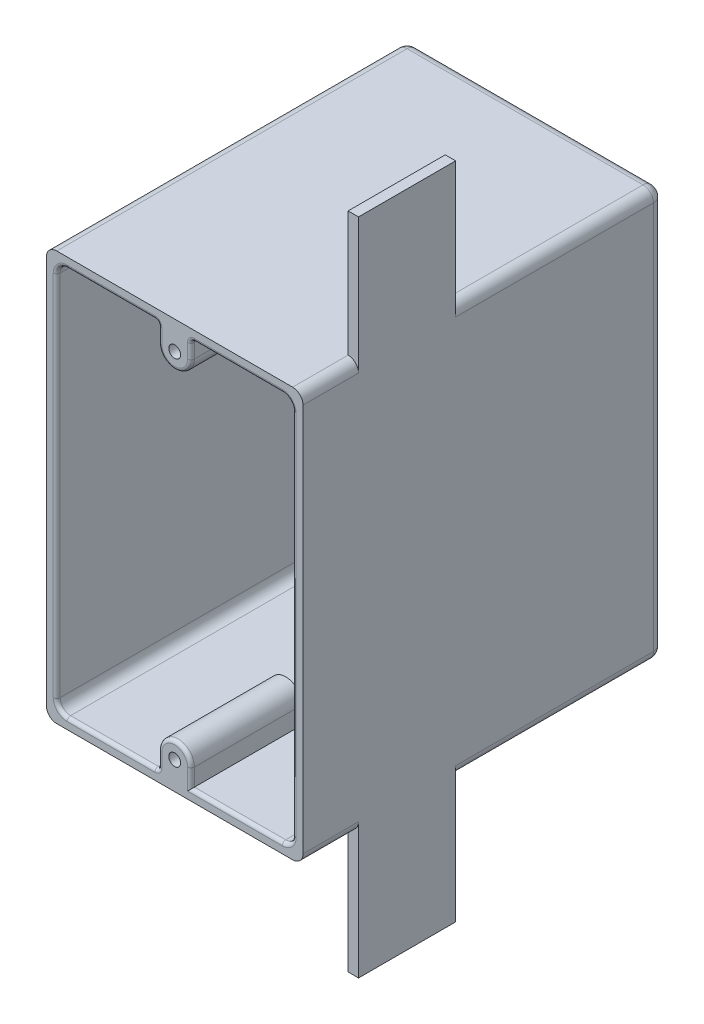
SolidWorks part; units mm, degrees
material "ABS"
ref_plane "Front" through (0, 0, 0) normal (0, 0, 1) x (1, 0, 0)
ref_plane "Top" through (0, 0, 0) normal (0, 1, 0) x (1, 0, 0)
ref_plane "Right" through (0, 0, 0) normal (1, 0, 0) x (0, 0, -1)
sketch "Sketch1" plane through (0, 0, 0) normal (0, 0, 1) x (1, 0, 0)
  line L1 (-29.3688, 46.8313) -> (29.3687, 46.8313)
  line L2 (-29.3688, 46.8313) -> (-29.3687, -46.8312)
  line L3 (-29.3687, -46.8312) -> (29.3687, -46.8312)
  line L4 (29.3687, 46.8313) -> (29.3687, -46.8312)
  line L5 (-29.3688, 46.8313) -> (29.3687, -46.8312) construction
  line L6 (-29.3687, -46.8312) -> (29.3687, 46.8313) construction
  point P0 (0, 0)
  dimension "D1" = 58.7375
  dimension "D2" = 93.6625
extrude "Back" add sketch "Sketch1" along normal blind 2.3813
sketch "Sketch2" plane through (0, 0, 2.3813) normal (0, 0, 1) x (1, 0, 0)
  line L24 (-26.9875, 44.45) -> (-26.9875, -44.45)
  line L25 (-29.3688, 46.8313) -> (29.3687, 46.8313)
  line L26 (-29.3688, 46.8313) -> (-29.3688, -46.8312)
  line L27 (-29.3688, -46.8312) -> (29.3687, -46.8312)
  line L28 (29.3687, 46.8313) -> (29.3687, -46.8312)
  line L29 (-26.9875, -44.45) -> (26.9875, -44.45)
  line L30 (26.9875, 44.45) -> (26.9875, -44.45)
  line L31 (-26.9875, 44.45) -> (26.9875, 44.45)
  dimension "D1" = 2.3813
extrude "Sides" add sketch "Sketch2" along normal blind 80.1688
sketch "Sketch6" plane through (0, 0, 82.55) normal (0, 0, 1) x (1, 0, 0)
  line L0 (29.3687, 46.8313) -> (-29.3688, 46.8313) construction
  line L1 (-29.3688, -46.8312) -> (29.3687, -46.8312) construction
  line L2 (-3.7338, 40.3793) -> (-3.7338, 44.45)
  line L3 (26.9875, 44.45) -> (-26.9875, 44.45) construction
  line L4 (3.7338, 40.3793) -> (3.7338, 44.45)
  line L5 (-3.7338, -40.4812) -> (-3.7338, -44.45)
  line L6 (-26.9875, -44.45) -> (26.9875, -44.45) construction
  line L7 (3.7338, -40.4812) -> (3.7338, -44.45)
  line L8 (-3.7338, 44.45) -> (3.7338, 44.45)
  line L9 (-3.7338, -44.45) -> (3.7338, -44.45)
  circle A0 centre (0, 40.3793) radius 1.3526
  circle A1 centre (0, -40.4812) radius 1.3526
  arc A2 (-3.7338, 40.3793) -> (3.7338, 40.3793) centre (0, 40.3793) ccw
  arc A3 (3.7338, -40.4812) -> (-3.7338, -40.4812) centre (0, -40.4812) ccw
  circle A4 centre (0, -40.4812) radius 3.7338 construction
  circle A5 centre (0, 40.3793) radius 3.7338 construction
  dimension "D1" = 2.7051
  dimension "D2" = 6.452
  dimension "D3" = 6.35
  dimension "D4" = 2.3813
extrude "Boss-Extrude6" add sketch "Sketch6" against normal blind 25.4
sketch "Sketch5" plane through (29.3687, 0, 0) normal (1, 0, 0) x (0, 0, -1)
  line L9 (-82.55, 46.8313) -> (0, 46.8313) construction
  line L10 (-69.85, 46.8313) -> (-47.625, 46.8313)
  line L11 (-69.85, 46.8313) -> (-69.85, 75.4063)
  line L12 (-69.85, 75.4063) -> (-47.625, 75.4063)
  line L13 (-47.625, 46.8313) -> (-47.625, 75.4063)
  line L14 (-82.55, -46.8312) -> (-82.55, 46.8313) construction
  line L15 (-82.55, -46.8312) -> (0, -46.8312) construction
  line L16 (-47.625, -75.4062) -> (-69.85, -75.4062)
  line L17 (-47.625, -75.4062) -> (-47.625, -46.8312)
  line L18 (-47.625, -46.8312) -> (-69.85, -46.8312)
  line L19 (-69.85, -75.4062) -> (-69.85, -46.8312)
  dimension "D1" = 22.225
  dimension "D2" = 28.575
  dimension "D3" = 12.7
extrude "Boss-Extrude5" add sketch "Sketch5" against normal blind 2.3813
fillet "Fillet4" radius 2.3813 18 edges at (26.9875, 0, 2.3813) (0, -44.45, 2.3813) (-26.9875, 0, 2.3813) (0, 44.45, 2.3813) (0, 46.8313, 0) (-29.3687, 0, 0) (0, -46.8312, 0) (29.3687, 0, 0) (-26.9875, -44.45, 42.4656) (-26.9875, 44.45, 42.4656) (26.9875, 44.45, 42.4656) (26.9875, -44.45, 42.4656) (29.3687, 46.8313, 23.8125) (29.3687, -46.8312, 23.8125) (29.3687, -46.8312, 76.2) (29.3687, 46.8313, 76.2) (-29.3687, -46.8312, 41.275) (-29.3688, 46.8313, 41.275)
fillet "Fillet5" radius 0.7937 20 edges at (3.7338, -42.4656, 82.55) (0, -36.7474, 82.55) (0, 36.6455, 82.55) (-3.7338, -42.4656, 82.55) (-3.7338, 42.4146, 82.55) (3.7338, 42.4146, 82.55) (14.17, -44.45, 82.55) (26.29, -43.7525, 82.55) (26.9875, 0, 82.55) (26.29, 43.7525, 82.55) (-14.17, -44.45, 82.55) (-26.29, -43.7525, 82.55) (-26.9875, 0, 82.55) (-26.29, 43.7525, 82.55) (-3.7338, 44.45, 69.85) (0, 44.45, 57.15) (3.7338, 44.45, 69.85) (14.17, 44.45, 82.55) (-14.17, 44.45, 82.55) (-3.7338, -44.45, 69.85)
